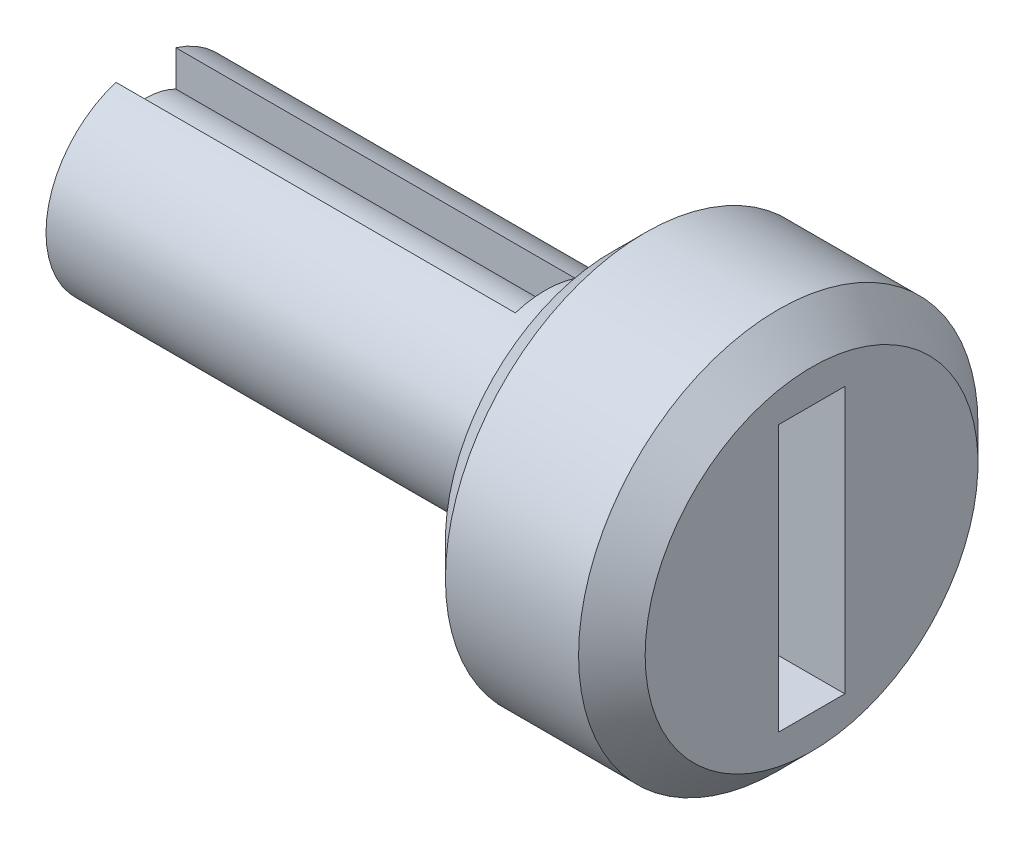
SolidWorks part; units mm, degrees
ref_plane "Front Plane" through (0, 0, 0) normal (0, 0, 1) x (1, 0, 0)
ref_plane "Top Plane" through (0, 0, 0) normal (0, 1, 0) x (1, 0, 0)
ref_plane "Right Plane" through (0, 0, 0) normal (1, 0, 0) x (0, 0, -1)
sketch "Sketch2" plane through (0, 0, 0) normal (0, 1, 0) x (1, 0, 0)
  line L0 (0, 0) -> (0, 3)
  line L1 (0, 3) -> (14, 3)
  line L2 (14, 3) -> (14, 6)
  line L3 (14, 6) -> (20, 6)
  line L4 (20, 6) -> (20, 0)
  line L5 (20, 0) -> (0, 0)
  line L6 (0, 0) -> (33.3109, 0) construction
  dimension "D1" = 20
  dimension "D2" = 6
  dimension "D3" = 6
  dimension "D4" = 12
revolve "Revolve1" add sketch "Sketch2" angle 360 about L6
sketch "Sketch3" plane through (0, 0, 0) normal (-1, 0, 0) x (0, 0, 1)
  circle A0 centre (0, 0) radius 1.2
  dimension "D1" = 2.4
extrude "Cut-Extrude1" cut sketch "Sketch3" against normal up to surface (14 mm away) up to face at (14, 0, 3)
cosmetic thread "Cosmetic Thread1" parameters "D2"=3
sketch "Sketch4" plane through (20, 0, 0) normal (1, 0, 0) x (0, 0, -1)
  line L1 (-1, -4) -> (1, -4)
  line L2 (-1, -4) -> (-1, 4)
  line L3 (-1, 4) -> (1, 4)
  line L4 (1, -4) -> (1, 4)
  line L5 (-1, -4) -> (1, 4) construction
  line L6 (-1, 4) -> (1, -4) construction
  point P0 (0, 0)
  dimension "D1" = 2
  dimension "D2" = 8
extrude "Cut-Extrude2" cut sketch "Sketch4" against normal blind 4
chamfer "Chamfer1" distance 1 angle 45 2 edges at (20, 0, 6) (14, 0, 6)
sketch "Sketch5" plane through (0, 0, 0) normal (-1, 0, 0) x (0, 0, 1)
  line L0 (-0.9, 2.3239) -> (0.9, 2.3239) construction
  line L1 (0, 2.3239) -> (0, 0) construction
  line L2 (-0.9, 2.8618) -> (-0.9, 1.7861)
  line L3 (0, 0) -> (0, -2.3239) construction
  line L4 (0.9, 2.8618) -> (0.9, 1.7861)
  line L5 (-0.9, -2.3239) -> (0.9, -2.3239) construction
  line L6 (-0.9, -1.7861) -> (-0.9, -2.8618)
  line L8 (0.9, -1.7861) -> (0.9, -2.8618)
  circle A0 centre (0, 0) radius 3 construction
  arc A1 (0.9, 2.8618) -> (-0.9, 2.8618) centre (0, 0) ccw
  arc A4 (-0.9, -2.8618) -> (0.9, -2.8618) centre (0, 0) ccw
  arc A6 (0.9, 1.7861) -> (-0.9, 1.7861) centre (0, 0) ccw
  arc A7 (-0.9, -1.7861) -> (0.9, -1.7861) centre (0, 0) ccw
  point P11 (0, -2.3239)
  dimension "D2" = 4
  dimension "D1" = 1.8
extrude "Cut-Extrude3" cut sketch "Sketch5" against normal offset from surface (12 mm away) 2 up to face at (14, 0, -5)
